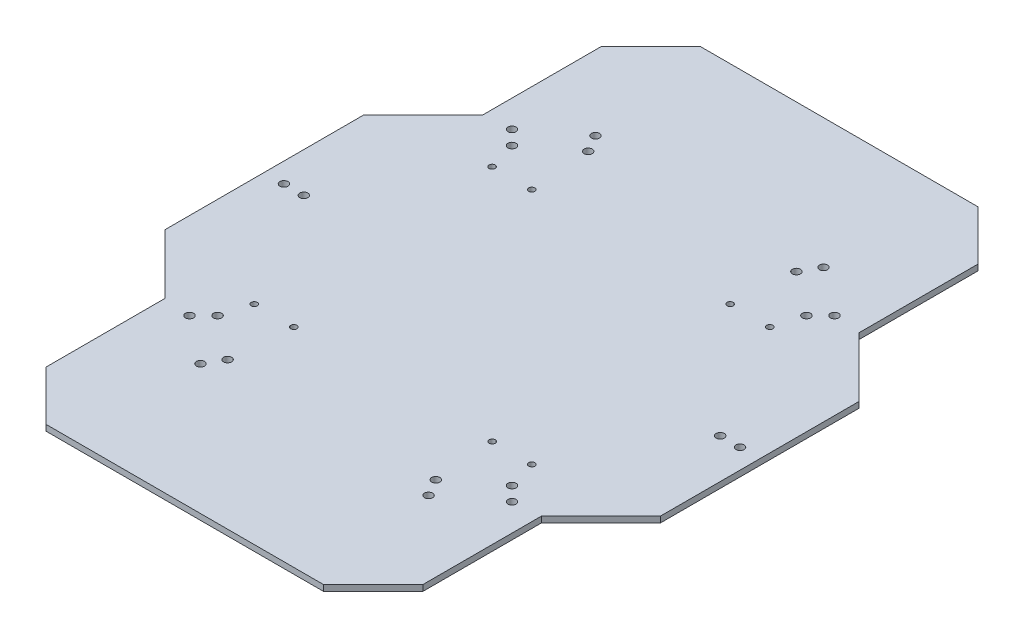
SolidWorks part; units mm, degrees
material "CF-ntbk"
ref_plane "Front Plane" through (0, 0, 0) normal (0, 0, 1) x (1, 0, 0)
ref_plane "Top Plane" through (0, 0, 0) normal (0, 1, 0) x (1, 0, 0)
ref_plane "Right Plane" through (0, 0, 0) normal (1, 0, 0) x (0, 0, -1)
sketch "Sketch1" plane through (0, 0, 0) normal (0, 1, 0) x (1, 0, 0)
  line L0 (-70, 165) -> (-95, 140)
  line L1 (-95, 140) -> (-95, 80)
  line L2 (-95, 80) -> (-125, 50)
  line L3 (-125, 50) -> (-125, -50)
  line L4 (-125, -50) -> (-95, -80)
  line L5 (-95, -80) -> (-95, -140)
  line L6 (-95, -140) -> (-70, -165)
  line L7 (-70, -165) -> (70, -165)
  line L8 (70, -165) -> (95, -140)
  line L9 (95, -140) -> (95, -80)
  line L10 (95, -80) -> (125, -50)
  line L11 (125, -50) -> (125, 50)
  line L12 (125, 50) -> (95, 80)
  line L13 (95, 80) -> (95, 140)
  line L14 (95, 140) -> (70, 165)
  line L15 (70, 165) -> (-70, 165)
  line L17 (-44.2539, 0) -> (44.2539, 0) construction
  line L18 (0, -44.7868) -> (0, 44.7868) construction
  dimension "D2" = 165
  dimension "D1" = 70
  dimension "D3" = 330
  dimension "D4" = 140
  dimension "D5" = 100
  dimension "D6" = 30
  dimension "D7" = 60
  dimension "D8" = 135
extrude "Boss-Extrude1" add sketch "Sketch1" along normal blind 3
sketch "Sketch2" plane through (0, 3, 0) normal (0, 1, 0) x (1, 0, 0)
  line L0 (-42.0339, -72.8048) -> (42.0339, 72.8048) construction
  line L2 (-40.506, 70.1585) -> (40.506, -70.1585) construction
  line L3 (0, -44.7868) -> (0, 44.7868) construction
  line L5 (-44.2539, 0) -> (44.2539, 0) construction
  line L6 (-71.0131, 0) -> (71.0131, 0) construction
  line L7 (-66.6695, -66.6695) -> (66.6695, 66.6695) construction
  line L8 (-57.0882, 57.0882) -> (57.0882, -57.0882) construction
  circle A0 centre (57.5, 99.5929) radius 2.05
  circle A1 centre (52.5, 90.9327) radius 2.05
  circle A2 centre (52.5, -90.9327) radius 2.05
  circle A3 centre (57.5, -99.5929) radius 2.05
  circle A4 centre (105, 0) radius 2.05
  circle A5 centre (115, 0) radius 2.05
  circle A6 centre (74.2462, 74.2462) radius 2.05
  circle A7 centre (81.3173, 81.3173) radius 2.05
  circle A8 centre (74.2462, -74.2462) radius 2.05
  circle A9 centre (81.3173, -81.3173) radius 2.05
  dimension "D1" = 4.1
  dimension "D2" = 10
  dimension "D4" = 105
  dimension "D3" = 30
  dimension "D5" = 30
  dimension "D6" = 10
  dimension "D7" = 105
  dimension "D8" = 10
  dimension "D9" = 105
  dimension "D10" = 45
  dimension "D11" = 45
  dimension "D12" = 10
  dimension "D13" = 105
  dimension "D14" = 10
  dimension "D15" = 105
extrude "Cut-Extrude1" cut sketch "Sketch2" against normal up to surface (3 mm away) up to face at (0, 0, 0)
mirror "Mirror1" about plane through (0, 0, 0) normal (1, 0, 0) of "Cut-Extrude1"
sketch "Sketch4" plane through (0, 3, 0) normal (0, 1, 0) x (1, 0, 0)
  line L0 (0, 121.6855) -> (0, -121.6855) construction
  line L1 (-91.1915, 0) -> (91.1915, 0) construction
  line L2 (-44.2539, 0) -> (44.2539, 0) construction
ref_point "Point1"
sketch "Sketch5" plane through (0, 3, 0) normal (0, 1, 0) x (1, 0, 0)
  line L0 (0, 121.6855) -> (0, -121.6855) construction
  line L1 (-91.1915, 0) -> (91.1915, 0) construction
  circle A0 centre (50, 60) radius 1.55
  circle A1 centre (70, 60) radius 1.55
  dimension "D1" = 3.1
  dimension "D2" = 20
  dimension "D3" = 50
  dimension "D4" = 60
  dimension "D5" = 60
extrude "Cut-Extrude2" cut sketch "Sketch5" against normal up to surface (3 mm away) up to face at (-57.5, 0, -97.5429)
pattern_linear "LPattern1" count 2 spacing 120 along (0, 0, 1) count 2 spacing 120 along (-1, 0, 0) of "Cut-Extrude2"
equation "\"ClampHoleDist\"= 10.00mm"
equation "\"D2@Sketch2\"=\"ClampHoleDist\""
equation "\"ClampDistMid\"=105"
equation "\"D13@Sketch2\"=\"ClampDistMid\""
equation "\"D9@Sketch2\"=\"ClampDistMid\""
equation "\"D4@Sketch2\"=\"ClampDistMid\""
equation "\"D15@Sketch2\"=\"ClampDistMid\""
equation "\"Length\"=330.000000"
equation "\"D3@Sketch1\"=\"Length\""
equation "\"Width\"=140.000000"
equation "\"D1@Sketch1\"=\"Width\"/2"
equation "\"D2@Sketch1\"=\"Length\"/2"
equation "\"D4@Sketch1\"=\"Width\""
equation "\"D7@Sketch1\"=(\"Length\"- 210)/2"
equation "\"D14@Sketch2\"=\"ClampHoleDist\""
equation "\"D8@Sketch2\"=\"ClampHoleDist\""
equation "\"D12@Sketch2\"=\"ClampHoleDist\""
equation "\"D6@Sketch2\"=\"ClampHoleDist\""
equation "\"HoleZDist\"=60.000000"
equation "\"D5@Sketch5\"=\"HoleZDist\""
equation "\"D4@Sketch5\"=\"HoleZDist\""
equation "\"HoleXDist\"=50.000000"
equation "\"D3@Sketch5\"=\"HoleXDist\""
equation "\"HoleSpacing\"=20"
equation "\"D2@Sketch5\"=\"HoleSpacing\""
equation "\"D3@LPattern1\"=\"HoleZDist\"*2"
equation "\"D4@LPattern1\"=\"HoleXDist\"*2+(\"HoleSpacing\")"
